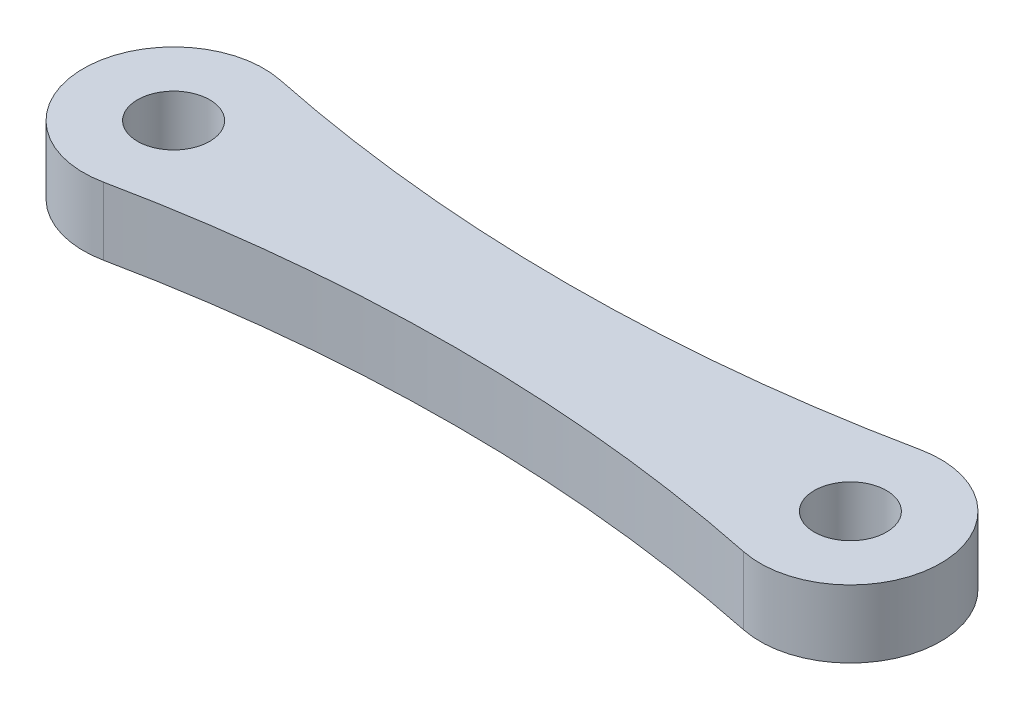
SolidWorks part; units mm, degrees
ref_plane "Front Plane" through (0, 0, 0) normal (0, 0, 1) x (1, 0, 0)
ref_plane "Top Plane" through (0, 0, 0) normal (0, 1, 0) x (1, 0, 0)
ref_plane "Right Plane" through (0, 0, 0) normal (1, 0, 0) x (0, 0, -1)
sketch "Sketch1" plane through (0, 0, 0) normal (0, 1, 0) x (1, 0, 0)
  line L0 (-7.5, 0) -> (7.5, 0) construction
  line L1 (-7.5, 2) -> (7.5, 2)
  line L2 (-7.5, -2) -> (7.5, -2)
  circle A0 centre (-7.5, 0) radius 0.8
  circle A1 centre (7.5, 0) radius 0.8
  arc A2 (-7.5, 2) -> (-7.5, -2) centre (-7.5, 0) ccw
  arc A3 (7.5, -2) -> (7.5, 2) centre (7.5, 0) ccw
  point P4 (0, 0)
  dimension "D2" = 1.6
  dimension "D4" = 4
  dimension "D1" = 15
extrude "Boss-Extrude1" add sketch "Sketch1" along normal blind 1.5
sketch "Sketch2" plane through (0, 1.5, 0) normal (0, 1, 0) x (1, 0, 0)
  line L0 (-7.5, 0) -> (7.5, 0) construction
  arc A0 (-7.0946, 1.9585) -> (-7.0946, -1.9585) centre (-7.5, 0) ccw
  arc A1 (7.0946, -1.9585) -> (7.0946, 1.9585) centre (7.5, 0) ccw
  arc A2 (-7.0946, 1.9585) -> (7.0946, 1.9585) centre (0, 36.2319) ccw
  arc A3 (-7.5, 2) -> (-7.5, -2) centre (-7.5, 0) ccw construction
  arc A4 (7.5, -2) -> (7.5, 2) centre (7.5, 0) ccw construction
  arc A5 (-7.0946, -1.9585) -> (7.0946, -1.9585) centre (0, -36.2319) cw
  dimension "D1" = 35
extrude "Cut-Extrude1" cut sketch "Sketch2" against normal through all flip side to cut
